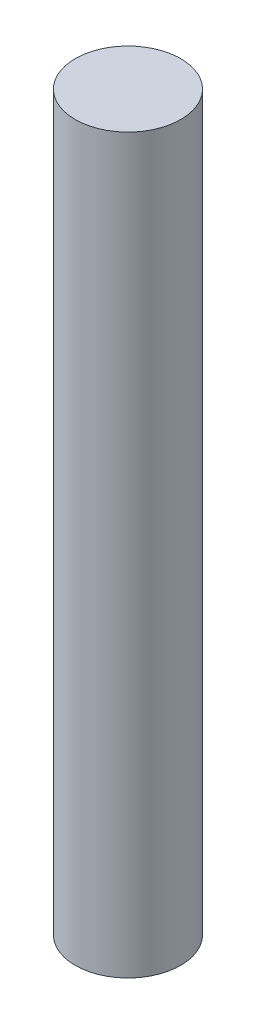
SolidWorks part; units mm, degrees
ref_plane "前视基准面" through (0, 0, 0) normal (0, 0, 1) x (1, 0, 0)
ref_plane "上视基准面" through (0, 0, 0) normal (0, 1, 0) x (1, 0, 0)
ref_plane "右视基准面" through (0, 0, 0) normal (1, 0, 0) x (0, 0, -1)
sketch "草图1" plane through (0, 0, 0) normal (0, 1, 0) x (1, 0, 0)
  circle A0 centre (0, 0) radius 1.8
extrude "凸台-拉伸1" add sketch "草图1" along normal blind 25
